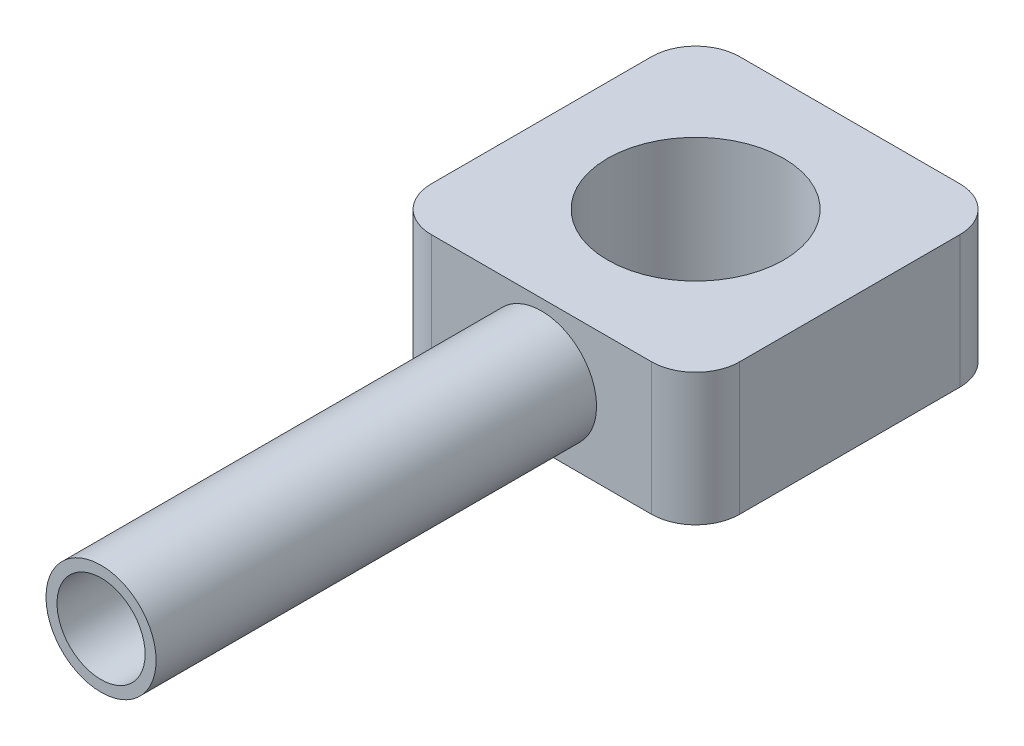
SolidWorks part; units mm, degrees
ref_plane "Front Plane" through (0, 0, 0) normal (0, 0, 1) x (1, 0, 0)
ref_plane "Top Plane" through (0, 0, 0) normal (0, 1, 0) x (1, 0, 0)
ref_plane "Right Plane" through (0, 0, 0) normal (1, 0, 0) x (0, 0, -1)
sketch "Sketch1" plane through (0, 0, 0) normal (0, 1, 0) x (1, 0, 0)
  line L1 (-125, 175) -> (125, 175)
  line L2 (-175, 125) -> (-175, -125)
  line L3 (-125, -175) -> (125, -175)
  line L4 (175, 125) -> (175, -125)
  line L5 (-175, 175) -> (175, -175) construction
  line L6 (-175, -175) -> (175, 175) construction
  circle A0 centre (0, 0) radius 100
  arc A1 (-125, -175) -> (-175, -125) centre (-125, -125) cw
  arc A2 (125, -175) -> (175, -125) centre (125, -125) ccw
  arc A3 (125, 175) -> (175, 125) centre (125, 125) cw
  arc A4 (-125, 175) -> (-175, 125) centre (-125, 125) ccw
  point P0 (0, 0)
  dimension "D1" = 200
  dimension "D4" = 50
  dimension "D2" = 350
  dimension "D3" = 350
extrude "Boss-Extrude1" add sketch "Sketch1" along normal blind 150
sketch "Sketch4" plane through (0, 0, 175) normal (0, 0, 1) x (1, 0, 0)
  circle A0 centre (0, 75) radius 62.5
  circle A1 centre (0, 75) radius 50
  dimension "D1" = 125
  dimension "D2" = 100
extrude "Boss-Extrude3" add sketch "Sketch4" along normal blind 500
